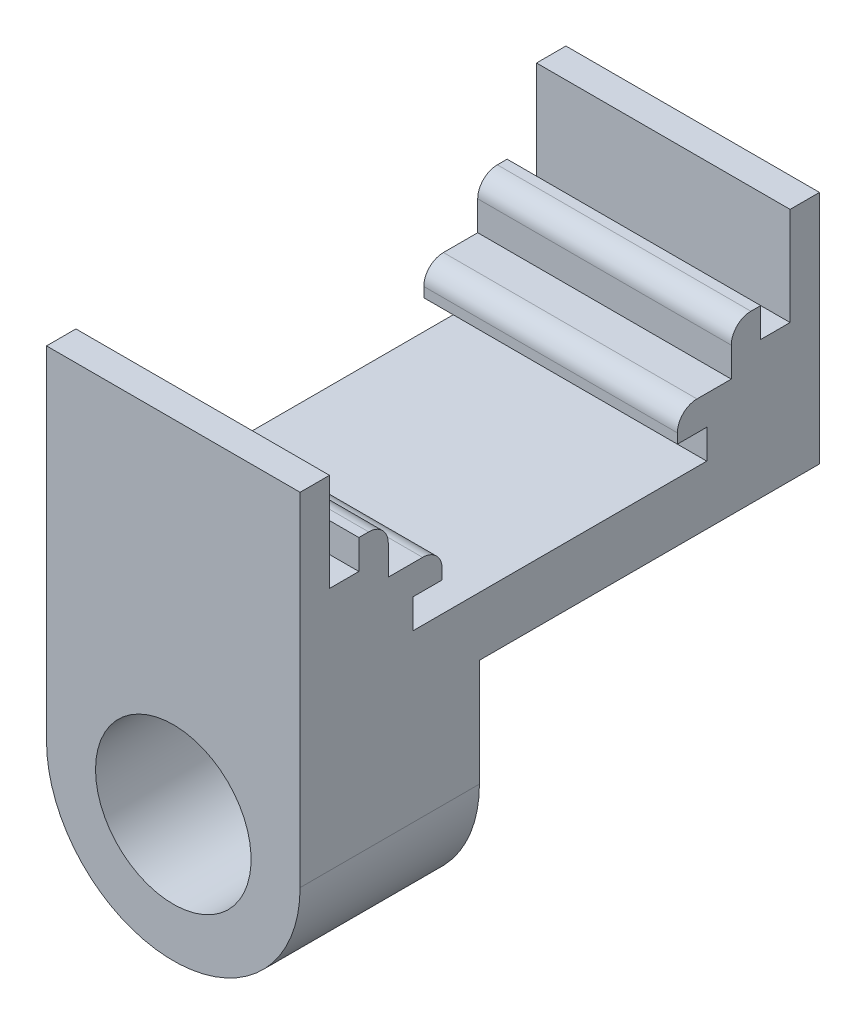
SolidWorks part; units mm, degrees
material "ABS"
ref_plane "Front Plane" through (0, 0, 0) normal (0, 0, 1) x (1, 0, 0)
ref_plane "Top Plane" through (0, 0, 0) normal (0, 1, 0) x (1, 0, 0)
ref_plane "Right Plane" through (0, 0, 0) normal (1, 0, 0) x (0, 0, -1)
sketch "Sketch1" plane through (0, 0, 0) normal (1, 0, 0) x (0, 0, -1)
  line L1 (-26.5, -27.5) -> (-26.5, -5.5)
  line L7 (-23.5, -5.5) -> (-23.5, -15.5)
  line L8 (-23.5, -15.5) -> (-20.5, -15.5)
  line L9 (-20.5, -15.5) -> (-20.5, -12.5)
  line L10 (-20.5, -12.5) -> (-17.5, -12.5)
  line L11 (-17.5, -12.5) -> (-17.5, -17.5)
  line L12 (-17.5, -17.5) -> (-12, -17.5)
  line L14 (-12, -20.5) -> (-15, -20.5)
  line L15 (-15, -20.5) -> (-15, -23.5)
  line L18 (-12, -20.5) -> (-12, -17.5)
  line L19 (0, -27.5) -> (0, -23.5) construction
  line L35 (-23.5, -5.5) -> (-26.5, -5.5)
  line L37 (0, -23.5) -> (0, -27.5) construction
  line L50 (-15, -23.5) -> (0, -23.5)
  line L51 (0, -23.5) -> (0, -27.5)
  line L52 (0, -27.5) -> (-26.5, -27.5)
  dimension "D1" = 3
  dimension "D2" = 3
  dimension "D3" = 3
  dimension "D4" = 20.5
  dimension "D5" = 15
  dimension "D6" = 3
  dimension "D7" = 20.5
  dimension "D8" = 0
  dimension "D9" = 3
  dimension "3" = 3
  dimension "D11" = 10
  dimension "D12" = 3
extrude "Boss-Extrude1" add sketch "Sketch1" along normal blind 25.875
fillet "Fillet1" radius 2 2 edges at (12.9375, -17.5, 12) (12.9375, -12.5, 17.5)
mirror "Mirror1" about plane through (25.875, -23.5, 0) normal (0, 0, 1) of bodies 101 108
sketch "Sketch2" plane through (0, 0, 26.5) normal (0, 0, -1) x (-1, 0, 0)
  line L2 (-25.875, -27.5) -> (-25.875, -40.4375)
  line L3 (0, -27.5) -> (0, -40.4375)
  line L4 (-25.875, -27.5) -> (-25.875, -23.5)
  line L5 (-25.875, -23.5) -> (0, -23.5)
  line L6 (0, -23.5) -> (0, -27.5)
  circle A0 centre (-12.9375, -40.4375) radius 7.9375
  arc A1 (-25.875, -40.4375) -> (0, -40.4375) centre (-12.9375, -40.4375) ccw
  point P2 (0, 0)
  point P3 (0, 0)
  point P4 (0, 0)
  dimension "D1" = 15.875
extrude "Boss-Extrude2" add sketch "Sketch2" along normal blind 18.3
sketch "Sketch3" plane through (0, -27.5, 0) normal (0, -1, 0) x (1, 0, 0)
  line L4 (25.875, -26.5) -> (25.875, 8.2)
  line L5 (25.875, 8.2) -> (0, 8.2)
  line L6 (0, 8.2) -> (0, -26.5)
  line L7 (0, -26.5) -> (25.875, -26.5)
  line L8 (25.875, -26.5) -> (25.875, 8.2)
  line L10 (0, 8.2) -> (0, -26.5)
  line L11 (0, -26.5) -> (25.875, -26.5)
  line L13 (25.875, 8.2) -> (0, 8.2)
  dimension "D1" = 0
extrude "Boss-Extrude3" add sketch "Sketch3" along normal blind 2
